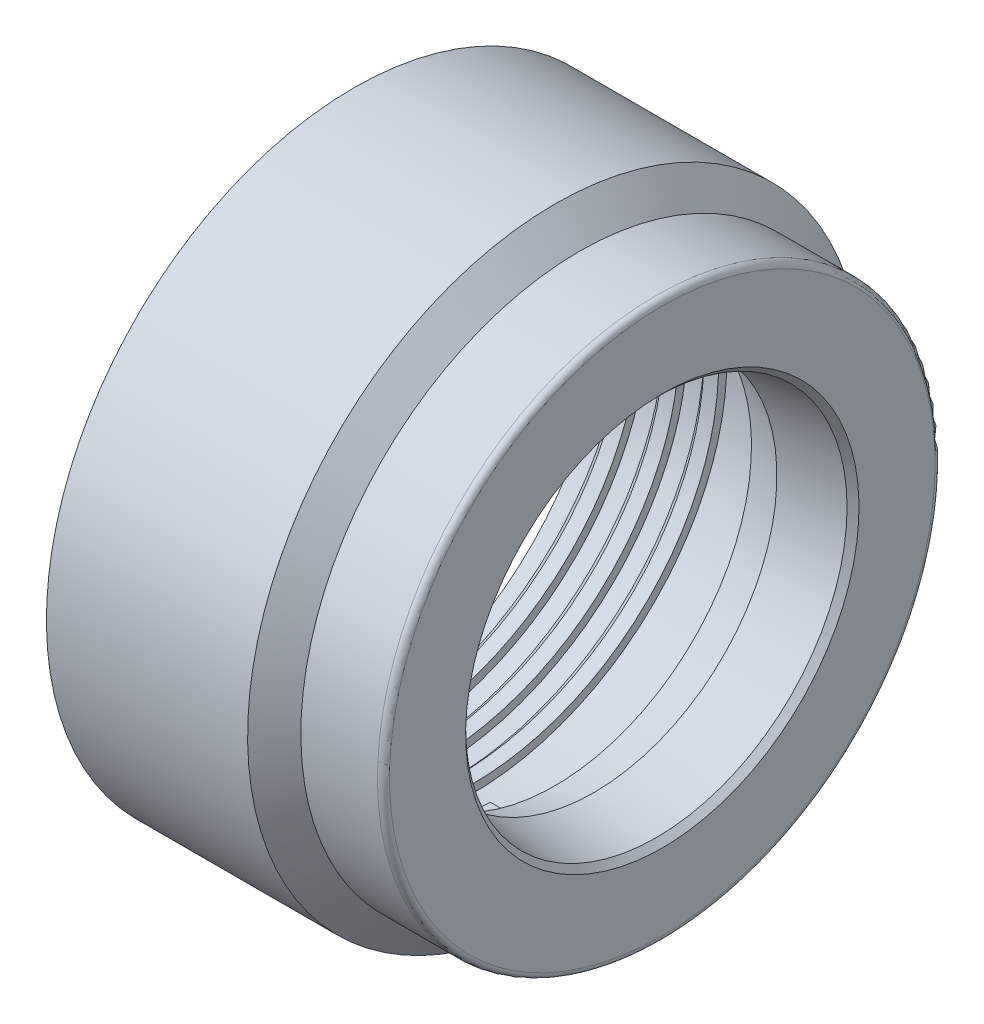
SolidWorks part; units mm, degrees
ref_plane "Front Plane" through (0, 0, 0) normal (0, 0, 1) x (1, 0, 0)
ref_plane "Top Plane" through (0, 0, 0) normal (0, 1, 0) x (1, 0, 0)
ref_plane "Right Plane" through (0, 0, 0) normal (1, 0, 0) x (0, 0, -1)
sketch "Sketch1" plane through (0, 0, 0) normal (0, 0, 1) x (1, 0, 0)
  line L0 (14.0477, 0) -> (14.0477, 22.86) construction
  line L1 (0, 3.7871) -> (-2.5126, 1.2745)
  line L2 (0, 3.7871) -> (0, 35.7587)
  line L3 (-2.54, 38.2987) -> (-34.7486, 38.2987)
  line L4 (-34.7486, 38.2987) -> (-45.139, 50.2964)
  line L5 (-45.139, 50.2964) -> (-129.7065, 50.2964)
  line L6 (-2.5126, 1.2745) -> (-28.748, -1.9913)
  line L7 (-28.748, -1.9913) -> (-28.748, 1.2745)
  line L8 (-28.748, 1.2745) -> (-45.139, 3.7249)
  line L9 (-45.139, 3.7249) -> (-45.139, 24.2453)
  line L11 (-129.7065, 50.2964) -> (-129.7065, 26.7853)
  line L16 (-3.8865, 1.1035) -> (-3.8865, -78.9065) construction
  line L17 (-3.8865, -78.9065) -> (-126.7969, -78.9065) construction
  line L20 (-129.7065, 26.7853) -> (-47.679, 26.7853)
  arc A0 (0, 35.7587) -> (-2.54, 38.2987) centre (-2.54, 35.7587) ccw
  arc A1 (-45.139, 24.2453) -> (-47.679, 26.7853) centre (-47.679, 24.2453) ccw
  point P12 (0, 0)
  point P15 (-129.7065, 27.1848)
  dimension "D2" = 2.54
  dimension "D3" = 2.54
  dimension "D1" = 22.86
  dimension "D4" = 80.01
revolve "Revolve1" add sketch "Sketch1" angle 360 about L17
ref_plane "Plane1" through (-66.2065, 0, 0) normal (-1, 0, 0) x (0, 0, 1)
sketch "Sketch3" plane through (-66.2065, 0, 0) normal (-1, 0, 0) x (0, 0, 1)
  circle A0 centre (0, -78.9065) radius 105.6917 construction
  circle A1 centre (0, -78.9065) radius 105.6917
curve "Helix/Spiral1" pitch 16.51 height 49.53 turns 3
sketch "Sketch4" plane through (0, 0, 0) normal (0, 0, 1) x (1, 0, 0)
  line L0 (-66.2065, -184.9072) -> (-76.1125, -184.9072)
  line L1 (-66.2065, 142.1231) -> (-66.2065, -142.1231) construction
  line L2 (-66.2065, -184.9072) -> (-66.2065, -181.0972)
  line L3 (-66.2065, -181.0972) -> (-72.3025, -181.0972)
  line L4 (-72.3025, -181.0972) -> (-76.1125, -184.9072)
  dimension "D1" = 9.906
  dimension "D2" = 3.81
  dimension "D3" = 6.096
sweep "Sweep1" add profiles "Sketch4" path "Helix/Spiral1"
